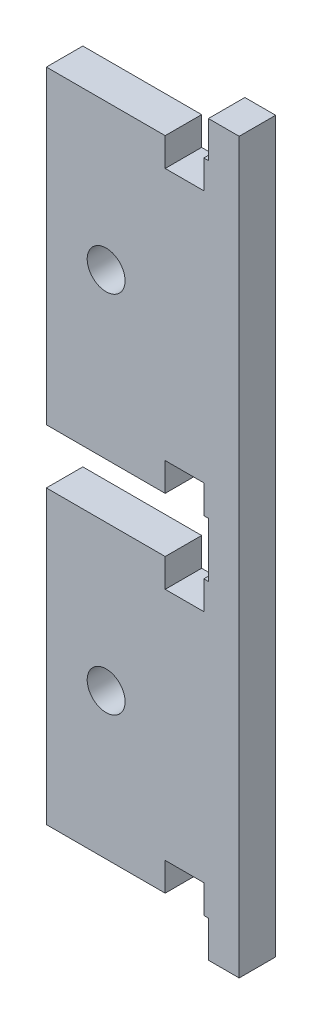
SolidWorks part; units mm, degrees
material "AISI 4130 Steel, annealed at 865C"
ref_plane "X-Y Datum" through (0, 0, 0) normal (0, 0, 1) x (1, 0, 0)
ref_plane "X-Z Datum" through (0, 0, 0) normal (0, 1, 0) x (1, 0, 0)
ref_plane "Y-Z Datum" through (0, 0, 0) normal (1, 0, 0) x (0, 0, -1)
sketch "Sketch2" plane through (0, 0, 0) normal (0, 0, 1) x (1, 0, 0)
  line L0 (32.9006, 127) -> (0, 127) construction
  line L1 (0, 0) -> (40.64, 0)
  line L2 (0, 0) -> (0, 127)
  line L3 (0, 127) -> (40.64, 127)
  line L4 (40.64, 0) -> (40.64, 127)
  point P7 (17.4625, 31.75)
  point P8 (17.4625, 95.25)
  dimension "D1" = 40.64
extrude "Boss-Extrude1" add sketch "Sketch2" along normal blind 6.35
hole_wizard "M6 Clearance Hole1" positions "Sketch3" profile "Sketch4" hole size "M6" standard "ANSI Metric" end condition through all
sketch "Sketch3" plane through (0, 0, 6.35) normal (0, 0, 1) x (1, 0, 0)
  point P0 (17.4625, 31.75)
  point P3 (17.4625, 95.25)
sketch "Sketch4" plane through (17.4625, 31.75, 6.35) normal (1, 0, 0) x (0, -1, 0)
  line L0 (0, 0) -> (0, 6.35)
  line L1 (0, 6.35) -> (3.3, 6.35)
  line L2 (3.3, 6.35) -> (3.3, 0)
  line L5 (3.3, 0) -> (0, 0)
  line L11 (0, -6.35) -> (0, 107.95) construction
  dimension "Thru Hole Dia." = 6.6
  dimension "Thru Hole Depth" = 6.35
sketch "Sketch5" plane through (0, 0, 6.35) normal (0, 0, 1) x (1, 0, 0)
  line L0 (7.0505, 127) -> (7.0505, 0)
  line L1 (40.64, 127) -> (0, 127) construction
  line L2 (0, 0) -> (40.64, 0) construction
  circle A0 centre (17.4625, 95.25) radius 3.3 construction
  point P6 (14.1625, 95.25)
  line M4 (0, 127) -> (0, 0)
  line M5 (0, 0) -> (40.64, 0)
  line M7 (40.64, 127) -> (0, 127)
  dimension "D1" = 7.112
extrude "Cut-Extrude1" cut sketch "Sketch5" against normal through all and the other way through all contours L0 M7 M4 M5
sketch "Sketch6" plane through (0, 0, 6.35) normal (0, 0, 1) x (1, 0, 0)
  line L0 (-3.175, 120.65) -> (36.0756, 120.65)
  line L1 (36.0756, 120.65) -> (36.0756, 130.175)
  line L2 (36.0756, 130.175) -> (-3.175, 130.175)
  line L3 (-3.175, 130.175) -> (-3.175, 120.65)
  line L4 (0, 123.825) -> (32.9006, 123.825)
  line L5 (32.9006, 123.825) -> (32.9006, 127)
  line L6 (32.9006, 127) -> (0, 127)
  line L7 (0, 127) -> (0, 123.825)
  line L8 (0, 123.825) -> (32.9006, 123.825)
  line L9 (32.9006, 123.825) -> (32.9006, 127)
  line L10 (32.9006, 127) -> (0, 127)
  line L11 (0, 127) -> (0, 123.825)
  line L16 (0, 60.325) -> (32.9006, 60.325)
  line L17 (32.9006, 60.325) -> (32.9006, 63.5)
  line L18 (32.9006, 63.5) -> (0, 63.5)
  line L19 (0, 63.5) -> (0, 60.325)
  line L24 (0, 0) -> (34.925, 0)
  line L25 (34.925, 0) -> (34.925, 3.175)
  line L26 (34.925, 3.175) -> (0, 3.175)
  line L27 (0, 3.175) -> (0, 0)
  line L28 (36.0756, 66.675) -> (-3.175, 66.675)
  line L29 (-3.175, 66.675) -> (-3.175, 57.15)
  line L30 (-3.175, 57.15) -> (36.0756, 57.15)
  line L31 (36.0756, 57.15) -> (36.0756, 66.675)
  line L32 (38.1, 6.35) -> (-3.175, 6.35)
  line L33 (-3.175, 6.35) -> (-3.175, -3.175)
  line L34 (-3.175, -3.175) -> (38.1, -3.175)
  line L35 (38.1, -3.175) -> (38.1, 6.35)
  line L36 (35.2819, 127) -> (35.2819, 0)
  line L37 (40.64, 127) -> (7.0505, 127) construction
  line L38 (7.0505, 0) -> (40.64, 0) construction
  line M19 (7.0505, 127) -> (7.0505, 0)
  line M20 (7.0505, 0) -> (40.64, 0)
  line M22 (40.64, 127) -> (7.0505, 127)
  dimension "D5" = 2.3813
  dimension "D1" = 0
  dimension "D4" = 3.175
extrude "Cut-Extrude2" cut sketch "Sketch6" against normal through all contours L36 L9 L8 L0 M22 M19 | L8 L9 M22 M19 | L36 L28 L18 L17 L16 L30 M19 | L17 L18 L16 M19 | L36 L32 L26 L25 M19 M20 | L25 L26 M19 M20
sketch "Sketch7" plane through (0, 0, 6.35) normal (0, 0, 1) x (1, 0, 0)
  line L0 (34.4805, 115.697) -> (27.7495, 115.697)
  line L5 (27.7495, 120.8405) -> (27.7495, 115.697)
  line L18 (34.29, 120.65) -> (27.94, 120.65)
  line L19 (34.29, 120.65) -> (34.29, 115.8875)
  line L20 (34.29, 115.8875) -> (27.94, 115.8875)
  line L21 (27.94, 120.65) -> (27.94, 115.8875)
  line L22 (34.29, 71.4375) -> (27.94, 71.4375)
  line L23 (34.29, 71.4375) -> (34.29, 66.675)
  line L24 (34.29, 66.675) -> (27.94, 66.675)
  line L25 (27.94, 71.4375) -> (27.94, 66.675)
  line L26 (34.29, 57.15) -> (27.94, 57.15)
  line L27 (34.29, 57.15) -> (34.29, 52.3875)
  line L28 (34.29, 52.3875) -> (27.94, 52.3875)
  line L29 (27.94, 57.15) -> (27.94, 52.3875)
  line L30 (34.29, 11.1125) -> (27.94, 11.1125)
  line L31 (34.29, 11.1125) -> (34.29, 6.35)
  line L32 (34.29, 6.35) -> (27.94, 6.35)
  line L33 (27.94, 11.1125) -> (27.94, 6.35)
  line L34 (34.4805, 120.8405) -> (27.7495, 120.8405)
  line L35 (34.4805, 120.8405) -> (34.4805, 115.697)
  line L36 (34.4805, 66.4845) -> (27.7495, 66.4845)
  line L37 (27.7495, 71.628) -> (27.7495, 66.4845)
  line L38 (34.4805, 71.628) -> (27.7495, 71.628)
  line L39 (34.4805, 71.628) -> (34.4805, 66.4845)
  line L40 (34.4805, 52.197) -> (27.7495, 52.197)
  line L41 (27.7495, 57.3405) -> (27.7495, 52.197)
  line L42 (34.4805, 57.3405) -> (27.7495, 57.3405)
  line L43 (34.4805, 57.3405) -> (34.4805, 52.197)
  line L44 (34.4805, 6.1595) -> (27.7495, 6.1595)
  line L45 (27.7495, 11.303) -> (27.7495, 6.1595)
  line L46 (34.4805, 11.303) -> (27.7495, 11.303)
  line L47 (34.4805, 11.303) -> (34.4805, 6.1595)
  line L48 (35.2819, 6.35) -> (7.0505, 6.35) construction
  line M4 (35.2819, 120.65) -> (7.0505, 120.65)
  line M6 (7.0505, 66.675) -> (35.2819, 66.675)
  line M8 (35.2819, 57.15) -> (7.0505, 57.15)
  line M10 (7.0505, 6.35) -> (35.2819, 6.35)
  dimension "D1" = 0.1905
extrude "Cut-Extrude3" cut sketch "Sketch7" against normal through all contours L30 L33 L31 M10 | L47 L46 L45 L33 L30 L31 M10 | L47 L45 L44 M10 | L29 L28 L27 M8 | L43 L27 L28 L29 L41 L40 M8 | L43 L42 L41 M8 | L39 L37 L36 M6 | L22 L25 L23 M6 | L39 L38 L37 L25 L22 L23 M6 | L21 L20 L19 M4 | L35 L19 L20 L21 L5 L0 M4 | L35 L34 L5 M4
